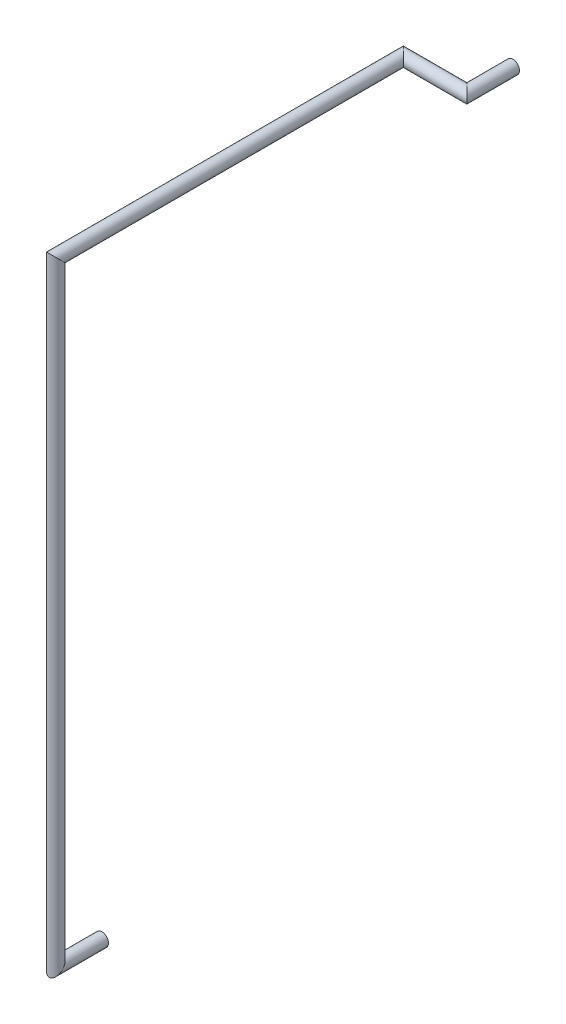
SolidWorks part; units mm, degrees
ref_plane "Plan de face" through (0, 0, 0) normal (0, 0, 1) x (1, 0, 0)
ref_plane "Plan de dessus" through (0, 0, 0) normal (0, 1, 0) x (1, 0, 0)
ref_plane "Plan de droite" through (0, 0, 0) normal (1, 0, 0) x (0, 0, -1)
sketch3d "Esquisse3D2"
  line L0 (0, 0, 0) -> (0, 0, 3.5)
  line L1 (0, 0, 3.5) -> (0, 46.6, 3.5)
  line L2 (0, 46.6, 3.5) -> (0, 46.6, -22.89)
  line L3 (0, 46.6, -22.89) -> (4.82, 46.6, -22.89)
  line L4 (4.82, 46.6, -22.89) -> (4.82, 46.6, -26.39)
  dimension "D1" = 3.5
  dimension "D2" = 46.6
  dimension "D3" = 26.39
  dimension "D4" = 3.5
  dimension "D5" = 4.82
sketch "Esquisse2" plane through (0, 0, 0) normal (0, 0, 1) x (1, 0, 0)
  circle A0 centre (0, 0) radius 0.5
  dimension "D1" = 1
sweep "Balayage2" add profiles "Esquisse2" path "Esquisse3D2"
